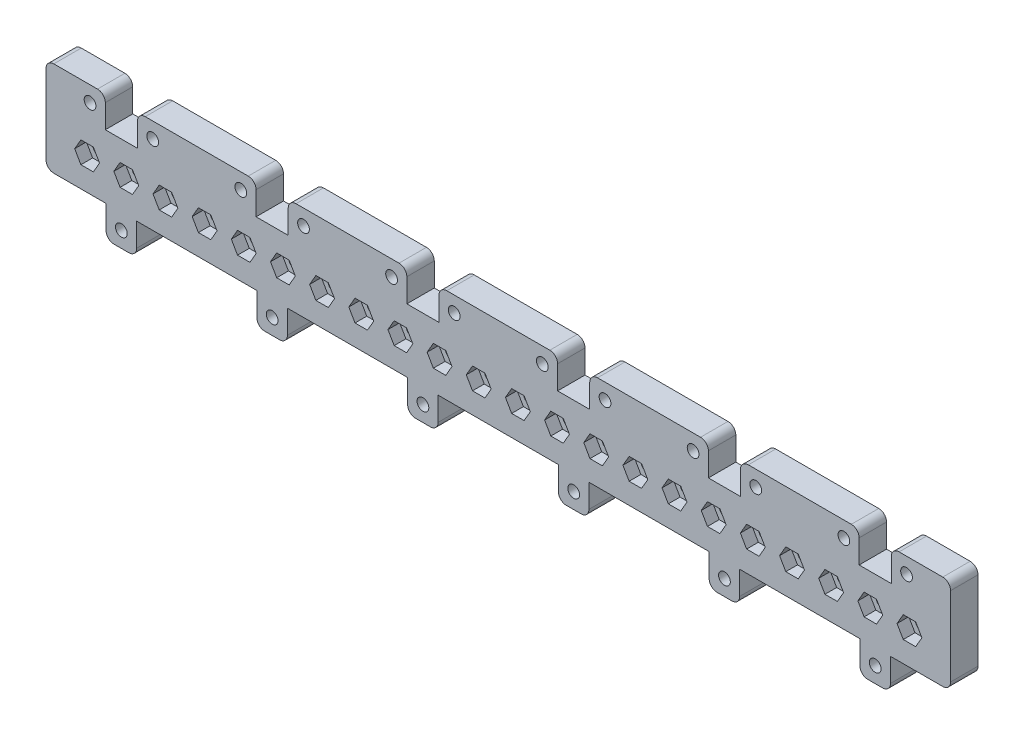
SolidWorks part; units mm, degrees
ref_plane "Front Plane" through (0, 0, 0) normal (0, 0, 1) x (1, 0, 0)
ref_plane "Top Plane" through (0, 0, 0) normal (0, 1, 0) x (1, 0, 0)
ref_plane "Right Plane" through (0, 0, 0) normal (1, 0, 0) x (0, 0, -1)
sketch "草图1" plane through (0, 0, 0) normal (0, 0, 1) x (1, 0, 0)
  line L1 (-115.5, -16.1) -> (115.5, -16.1)
  line L2 (-115.5, -16.1) -> (-115.5, 16.1)
  line L3 (-115.5, 16.1) -> (115.5, 16.1)
  line L4 (115.5, -16.1) -> (115.5, 16.1)
  line L5 (-115.5, -16.1) -> (115.5, 16.1) construction
  line L6 (-115.5, 16.1) -> (115.5, -16.1) construction
  point P0 (0, 0)
  dimension "D1" = 32.2
  dimension "D2" = 231
extrude "凸台-拉伸1" add sketch "草图1" along normal blind 7
sketch "草图4" plane through (0, 0, 0) normal (0, 0, -1) x (-1, 0, 0)
  line L6 (-65.75, 12.1) -> (-49.75, 12.1) construction
  circle A0 centre (-65.75, 12.1) radius 1.5
  circle A1 centre (-57.75, 12.1) radius 1.5
  circle A2 centre (-49.75, 12.1) radius 1.5
  point P0 (-57.75, 12.1)
  point P8 (-57.75, 12.1)
  dimension "D2" = 3
  dimension "D4" = 3
  dimension "D5" = 3
  dimension "D1" = 16
  dimension "D3" = 57.75
  dimension "D6" = 12.1
extrude "切除-拉伸3" cut sketch "草图4" against normal through all
sketch "草图9" plane through (0, 0, 0) normal (0, 0, -1) x (-1, 0, 0)
  circle A0 centre (-65.75, 12.1) radius 3
  circle A1 centre (-57.75, 12.1) radius 3
  circle A2 centre (-49.75, 12.1) radius 3
  dimension "D1" = 6
  dimension "D2" = 6
  dimension "D3" = 6
extrude "切除-拉伸7" cut sketch "草图9" against normal blind 3
pattern_linear "阵列(线性)2" count 5 spacing 38.5 along (-1, 0, 0) count 2 spacing 38.5 along (1, 0, 0) of "切除-拉伸3", "切除-拉伸7"
pattern_linear "阵列(线性)3" count 2 spacing 24.2 along (0, -1, 0) of "阵列(线性)2", "切除-拉伸3", "切除-拉伸7"
sketch "草图12" plane through (0, 0, 0) normal (0, 0, 1) x (1, 0, 0)
  line L0 (115.5, 16.1) -> (-115.5, 16.1) construction
  line L1 (-100.35, 16.1) -> (-92.15, 16.1)
  line L2 (-100.35, 16.1) -> (-100.35, 8.1)
  line L3 (-100.35, 8.1) -> (-92.15, 8.1)
  line L4 (-92.15, 16.1) -> (-92.15, 8.1)
  line L5 (-96.25, -988.2415) -> (-96.25, 49011.7585) construction
  line L6 (-115.5, -16.1) -> (115.5, -16.1) construction
  line L7 (-100.15, -16.1) -> (-115.5, -16.1)
  line L8 (-100.15, -16.1) -> (-100.15, -8.1)
  line L9 (-100.15, -8.1) -> (-115.5, -8.1)
  line L10 (-115.5, -16.1) -> (-115.5, -8.1)
  line L11 (-100.15, -8.1) -> (-92.35, -8.1) construction
  line L12 (-92.35, -16.1) -> (-77, -16.1)
  line L13 (-92.35, -16.1) -> (-92.35, -8.1)
  line L14 (-92.35, -8.1) -> (-77, -8.1)
  line L15 (-77, -16.1) -> (-77, -8.1)
  point P7 (-96.25, 16.1)
  point P21 (-96.25, -8.1)
  dimension "D1" = 8
  dimension "D2" = 8.2
  dimension "D3" = 7.8
  dimension "D4" = 8
  dimension "D5" = 38.5
extrude "切除-拉伸13" cut sketch "草图12" along normal blind 10
pattern_linear "阵列(线性)5" count 6 spacing 38.5 along (1, 0, 0) count 6 spacing 38.5 of "切除-拉伸13"
fillet "圆角3" radius 2 28 edges at (-115.5, 16.1, 3.5) (115.5, 16.1, 3.5) (-61.65, -16.1, 3.5) (-53.85, -16.1, 3.5) (-100.15, -16.1, 3.5) (-92.35, -16.1, 3.5) (-23.15, -16.1, 3.5) (-15.35, -16.1, 3.5) (15.35, -16.1, 3.5) (23.15, -16.1, 3.5) (53.85, -16.1, 3.5) (61.65, -16.1, 3.5) (100.15, -16.1, 3.5) (92.35, -16.1, 3.5) (-15.15, 16.1, 3.5) (-92.15, 16.1, 3.5) (-53.65, 16.1, 3.5) (23.35, 16.1, 3.5) (61.85, 16.1, 3.5) (100.35, 16.1, 3.5) (-100.35, 16.1, 3.5) (-61.85, 16.1, 3.5) (-23.35, 16.1, 3.5) (15.15, 16.1, 3.5) (53.65, 16.1, 3.5) (92.15, 16.1, 3.5) (115.5, -8.1, 3.5) (-115.5, -8.1, 3.5)
sketch "草图10" plane through (0, 0, 7) normal (0, 0, 1) x (1, 0, 0)
  circle A1 centre (-5, 0) radius 1.5
  dimension "D1" = 5
  dimension "D2" = 3
sketch "草图11" plane through (0, 0, 7) normal (0, 0, 1) x (1, 0, 0)
  line L7 (-1.8246, 0) -> (-3.4123, 2.75)
  line L8 (-3.4123, 2.75) -> (-6.5877, 2.75)
  line L9 (-6.5877, 2.75) -> (-8.1754, 0)
  line L10 (-8.1754, 0) -> (-6.5877, -2.75)
  line L11 (-6.5877, -2.75) -> (-3.4123, -2.75)
  line L12 (-3.4123, -2.75) -> (-1.8246, 0)
  circle A0 centre (-5, 0) radius 2.75 construction
  dimension "D1" = 5.5
extrude "切除-拉伸8" cut sketch "草图10" against normal through all
extrude "切除-拉伸9" cut sketch "草图11" against normal blind 3
pattern_linear "阵列(线性)4" count 12 spacing 10 along (1, 0, 0) count 11 spacing 10 along (-1, 0, 0) of "切除-拉伸9", "切除-拉伸8"
